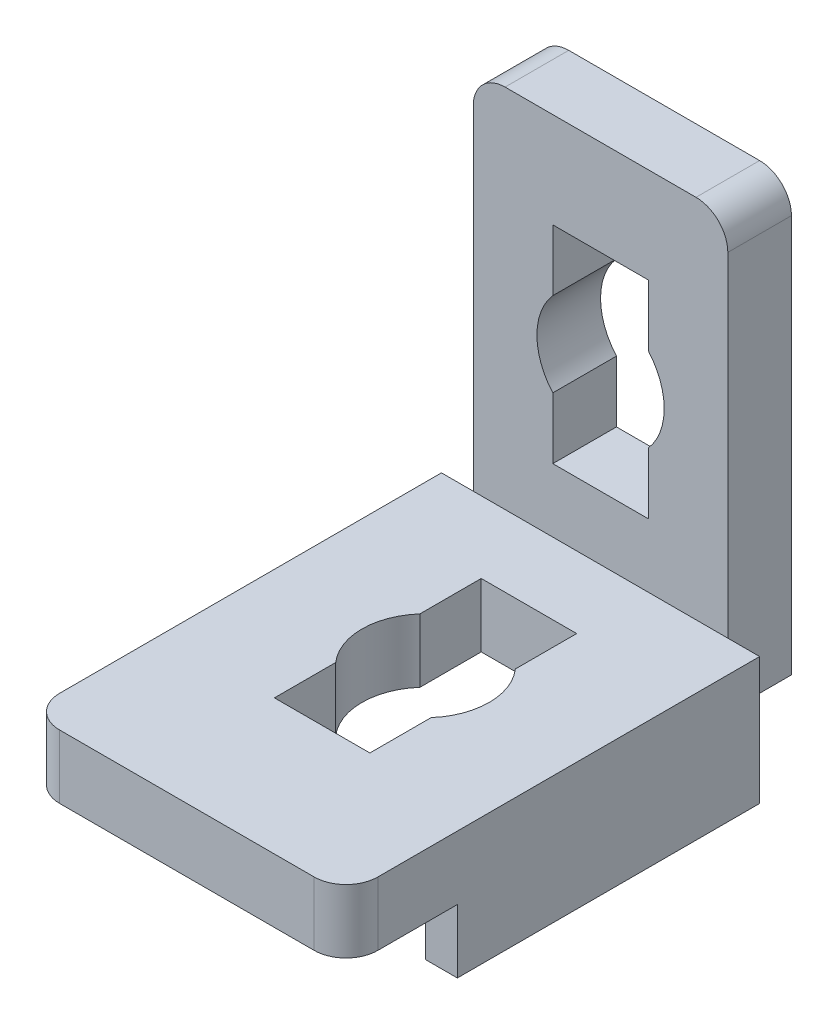
SolidWorks part; units mm, degrees
ref_plane "前视基准面" through (0, 0, 0) normal (0, 0, 1) x (1, 0, 0)
ref_plane "上视基准面" through (0, 0, 0) normal (0, 1, 0) x (1, 0, 0)
ref_plane "右视基准面" through (0, 0, 0) normal (1, 0, 0) x (0, 0, -1)
sketch "草图1" plane through (0, 0, 0) normal (0, 0, 1) x (1, 0, 0)
  line L1 (-4, 0) -> (4, 0)
  line L2 (-4, 0) -> (-4, 13.5)
  line L3 (-4, 13.5) -> (4, 13.5)
  line L4 (4, 0) -> (4, 13.5)
extrude "凸台-拉伸1" add sketch "草图1" along normal blind 2
sketch "草图2" plane through (0, 0, 0) normal (0, -1, 0) x (-1, 0, 0)
  line L0 (-4, -2) -> (-5, -2)
  line L1 (4, 0) -> (-4, 0)
  line L2 (4, 0) -> (4, -2)
  line L4 (-4, 0) -> (-4, -2)
  line L5 (5, -2) -> (4, -2)
  line L6 (5, -2) -> (5, -15)
  line L7 (5, -15) -> (-5, -15)
  line L8 (-5, -2) -> (-5, -15)
extrude "凸台-拉伸2" add sketch "草图2" against normal blind 2
sketch "草图3" plane through (0, 0, 0) normal (0, -1, 0) x (-1, 0, 0)
  line L1 (5, -2) -> (4, -2)
  line L2 (5, -2) -> (5, -11.5)
  line L3 (5, -11.5) -> (4, -11.5)
  line L4 (4, -2) -> (4, -11.5)
  line L5 (-5, -2) -> (-4, -2)
  line L6 (-5, -2) -> (-5, -11.5)
  line L7 (-5, -11.5) -> (-4, -11.5)
  line L8 (-4, -2) -> (-4, -11.5)
extrude "凸台-拉伸3" add sketch "草图3" along normal blind 2
sketch "草图4" plane through (0, 0, 0) normal (0, -1, 0) x (-1, 0, 0)
  line L0 (1.5, -8.8229) -> (1.5, -10.75)
  line L1 (1.5, -4.25) -> (-1.5, -4.25)
  line L2 (1.5, -4.25) -> (1.5, -6.1771)
  line L3 (1.5, -10.75) -> (-1.5, -10.75)
  line L4 (-1.5, -4.25) -> (-1.5, -6.1771)
  line L5 (-1.5, -8.8229) -> (-1.5, -10.75)
  arc A0 (1.5, -8.8229) -> (1.5, -6.1771) centre (0, -7.5) ccw
  arc A1 (-1.5, -6.1771) -> (-1.5, -8.8229) centre (0, -7.5) ccw
extrude "切除-拉伸1" cut sketch "草图4" against normal up to next
sketch "草图5" plane through (0, 0, 2) normal (0, 0, 1) x (1, 0, 0)
  line L0 (-1.5, 8.5729) -> (-1.5, 10.5)
  line L1 (-1.5, 4) -> (1.5, 4)
  line L2 (-1.5, 4) -> (-1.5, 5.9271)
  line L3 (-1.5, 10.5) -> (1.5, 10.5)
  line L4 (1.5, 4) -> (1.5, 5.9271)
  line L5 (1.5, 8.5729) -> (1.5, 10.5)
  arc A0 (-1.5, 8.5729) -> (-1.5, 5.9271) centre (0, 7.25) ccw
  arc A1 (1.5, 5.9271) -> (1.5, 8.5729) centre (0, 7.25) ccw
extrude "切除-拉伸2" cut sketch "草图5" against normal up to next
fillet "圆角1" radius 1 4 edges at (-5, 1, 15) (5, 1, 15) (-4, 13.5, 1) (4, 13.5, 1)
